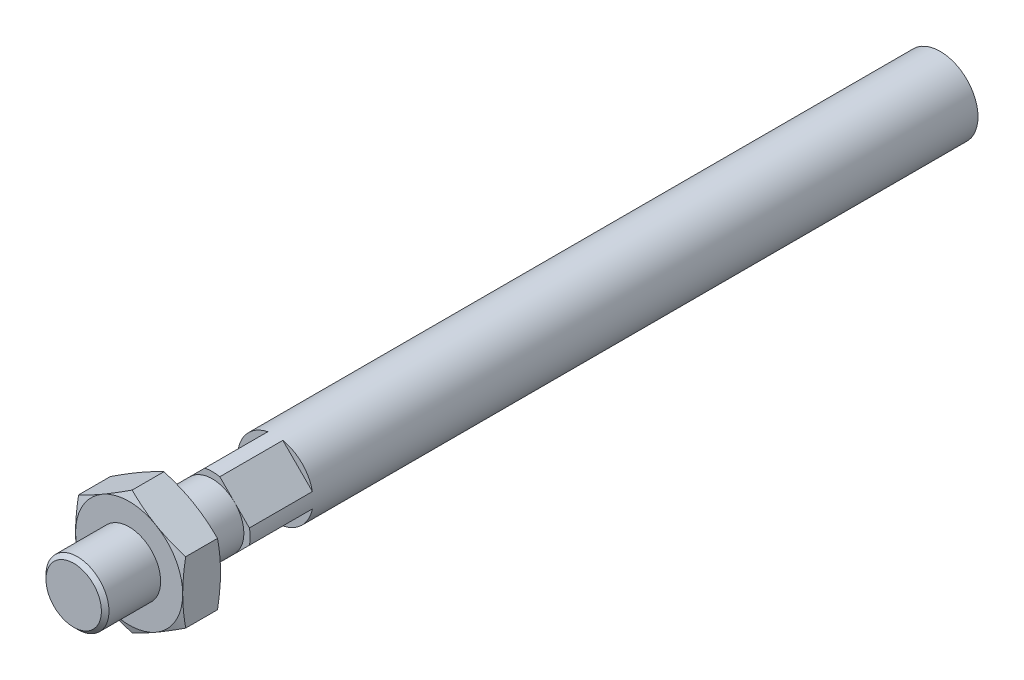
SolidWorks part; units mm, degrees
ref_plane "前视基准面" through (0, 0, 0) normal (0, 0, 1) x (1, 0, 0)
ref_plane "上视基准面" through (0, 0, 0) normal (0, 1, 0) x (1, 0, 0)
ref_plane "右视基准面" through (0, 0, 0) normal (1, 0, 0) x (0, 0, -1)
sketch "草图1" plane through (0, 0, 0) normal (1, 0, 0) x (0, 0, -1)
  line L0 (-59, 0) -> (59, 0) construction
  line L1 (0, 0) -> (0, 22.5) construction
  line L3 (-59, 0) -> (-59, 14) construction
  line L4 (-59, 14) -> (-68, 14) construction
  line L5 (-68, 14) -> (-68, 12.6) construction
  line L6 (-68, 12.6) -> (-74, 12.6) construction
  line L7 (-74, 12.6) -> (-74, 0) construction
  line L8 (25, 22.5) -> (118, 22.5) construction
  line L9 (-106, 0) -> (-106, 5) construction
  line L10 (-84, 0) -> (-106, 0) construction
  circle A0 centre (45, -5.5) radius 4.8645
  circle A1 centre (39, 6.5) radius 4
  point P2 (-106, 0)
  point P6 (-31.5, 0)
  point P10 (45, -5.5)
  point P11 (39, 6.5)
  point P20 (31.5, 0)
  point P21 (-74, 6)
  point P22 (25, 22.5)
  point P25 (-97.2, 0)
  point P28 (-91.2, 0)
  point P29 (-49.5, 0)
  dimension "D1" = 25.2
  dimension "O" = 9.729
  dimension "D3" = 8
  dimension "C" = 118
  dimension "S" = 45
  dimension "G" = 27.5
  dimension "N" = 14
  dimension "P" = 5.5
  dimension "Q" = 6
  dimension "R" = 6.5
  dimension "D" = 28
  dimension "F" = 15
  dimension "D2" = 9
  dimension "D4" = 8.8
  dimension "V" = 12
  dimension "行程" = 25
  dimension "C用" = 93
  dimension "B" = 47
  dimension "H" = 22
  dimension "J" = 6
  dimension "K" = 10
  dimension "M" = 9.5
sketch "草图2" plane through (0, 0, 0) normal (0, 0, 1) x (1, 0, 0)
  line L0 (0, 0) -> (0, 22.5) construction
  line L1 (-20.25, -22.5) -> (20.25, -22.5)
  line L2 (-22.5, -20.25) -> (-22.5, 20.25)
  line L3 (-20.25, 22.5) -> (20.25, 22.5)
  line L4 (22.5, -20.25) -> (22.5, 20.25)
  line L5 (-22.5, -22.5) -> (22.5, 22.5) construction
  line L6 (-22.5, 22.5) -> (22.5, -22.5) construction
  line L8 (0, 9.815) -> (-8.5, 4.9075)
  line L9 (-8.5, 4.9075) -> (-8.5, -4.9075)
  line L10 (-8.5, -4.9075) -> (0, -9.815)
  line L11 (0, -9.815) -> (8.5, -4.9075)
  line L12 (8.5, -4.9075) -> (8.5, 4.9075)
  line L13 (8.5, 4.9075) -> (0, 9.815)
  line L14 (0, 7.0711) -> (-7.0711, 0)
  line L15 (-7.0711, 0) -> (0, -7.0711)
  line L16 (0, -7.0711) -> (7.0711, 0)
  line L17 (7.0711, 0) -> (0, 7.0711)
  arc A0 (20.25, 22.5) -> (22.5, 20.25) centre (20.25, 20.25) cw
  arc A1 (20.25, -22.5) -> (22.5, -20.25) centre (20.25, -20.25) ccw
  arc A2 (-20.25, -22.5) -> (-22.5, -20.25) centre (-20.25, -20.25) cw
  arc A3 (-22.5, 20.25) -> (-20.25, 22.5) centre (-20.25, 20.25) cw
  circle A4 centre (-16.5, 16.5) radius 3
  circle A5 centre (0, 0) radius 8.5 construction
  circle A6 centre (0, 0) radius 5 construction
  point P0 (0, 0)
  point P19 (-16.5, 16.5)
  dimension "D1" = 2.25
  dimension "L" = 6
  dimension "I" = 17
  dimension "W" = 10
  dimension "T" = 33
sketch "行程" plane through (0, 0, 0) normal (1, 0, 0) x (0, 0, -1)
  line L0 (31.5, 0) -> (6.5, 0)
  line L1 (-59, 0) -> (59, 0) construction
  dimension "D1" = 25
sketch "草图3" plane through (0, 0, 0) normal (0, 0, 1) x (1, 0, 0)
  circle A0 centre (0, 0) radius 6
extrude "凸台-拉伸1" add sketch "草图3" against normal up to vertex (31.5 mm away) from vertex at 84 starting at point (0, 0, 84)
sketch "草图4" plane through (0, 0, 84) normal (0, 0, 1) x (1, 0, 0)
  circle A0 centre (0, 0) radius 5
extrude "凸台-拉伸2" add sketch "草图4" along normal up to vertex (22 mm away) up to point (0, 0, 106)
cosmetic thread "装饰螺纹线1" parameters "D2"=8.5
cosmetic thread "装饰螺纹线2" parameters "D2"=5
sketch "草图5" plane through (0, 0, 0) normal (0, 0, 1) x (1, 0, 0)
  line L0 (0, -9.815) -> (8.5, -4.9075) construction
  line L1 (8.5, -4.9075) -> (8.5, 4.9075) construction
  line L2 (8.5, 4.9075) -> (0, 9.815) construction
  line L3 (0, 9.815) -> (-8.5, 4.9075) construction
  line L4 (-8.5, 4.9075) -> (-8.5, -4.9075) construction
  line L5 (-8.5, -4.9075) -> (0, -9.815) construction
  line L6 (0, -9.815) -> (8.5, -4.9075)
  line L7 (8.5, -4.9075) -> (8.5, 4.9075)
  line L8 (8.5, 4.9075) -> (0, 9.815)
  line L9 (0, 9.815) -> (-8.5, 4.9075)
  line L10 (-8.5, 4.9075) -> (-8.5, -4.9075)
  line L11 (-8.5, -4.9075) -> (0, -9.815)
extrude "凸台-拉伸3" add sketch "草图5" along normal up to vertex (97.2 mm away) from vertex at 91.2 starting at point (0, 0, 91.2)
sketch "草图7" plane through (0, 0, 0) normal (0, 1, 0) x (0, 0, -1)
  line L0 (-97.2, 8.5) -> (-97.2, 18.7424)
  line L1 (-97.2, 8.5) -> (-94.2, 16.7424)
  line L2 (-97.2, 0) -> (-97.2, 8.5) construction
  line L5 (-91.2, 8.5) -> (-94.2, 16.7424)
  line L6 (-91.2, 8.5) -> (-91.2, 18.7424)
  line L7 (-97.2, 18.7424) -> (-91.2, 18.7424)
  line L8 (-91.2, 0) -> (-91.2, 8.5) construction
  line L9 (-94.2, 8.5) -> (-94.2, 0) construction
  line L10 (-97.2, 8.5) -> (-91.2, 8.5) construction
  line L11 (-84, 0) -> (-106, 0) construction
  dimension "D1" = 20
  dimension "D2" = 2
revolve "切除-旋转2" cut sketch "草图7" angle 360 mid plane about L10
sketch "草图6" plane through (0, 0, 84) normal (0, 0, 1) x (1, 0, 0)
  line L0 (0, -7.0711) -> (7.0711, 0) construction
  line L1 (7.0711, 0) -> (0, 7.0711) construction
  line L2 (0, 7.0711) -> (-7.0711, 0) construction
  line L3 (-7.0711, 0) -> (0, -7.0711) construction
  line L4 (0, -7.0711) -> (7.0711, 0)
  line L5 (7.0711, 0) -> (0, 7.0711)
  line L6 (0, 7.0711) -> (-7.0711, 0)
  line L7 (-7.0711, 0) -> (0, -7.0711)
extrude "切除-拉伸1" cut sketch "草图6" against normal up to vertex (10 mm away) flip side to cut up to point (0, 0, 74)
chamfer "倒角1" distance 0.6 angle 45 1 edges at (5, 0, 106)
